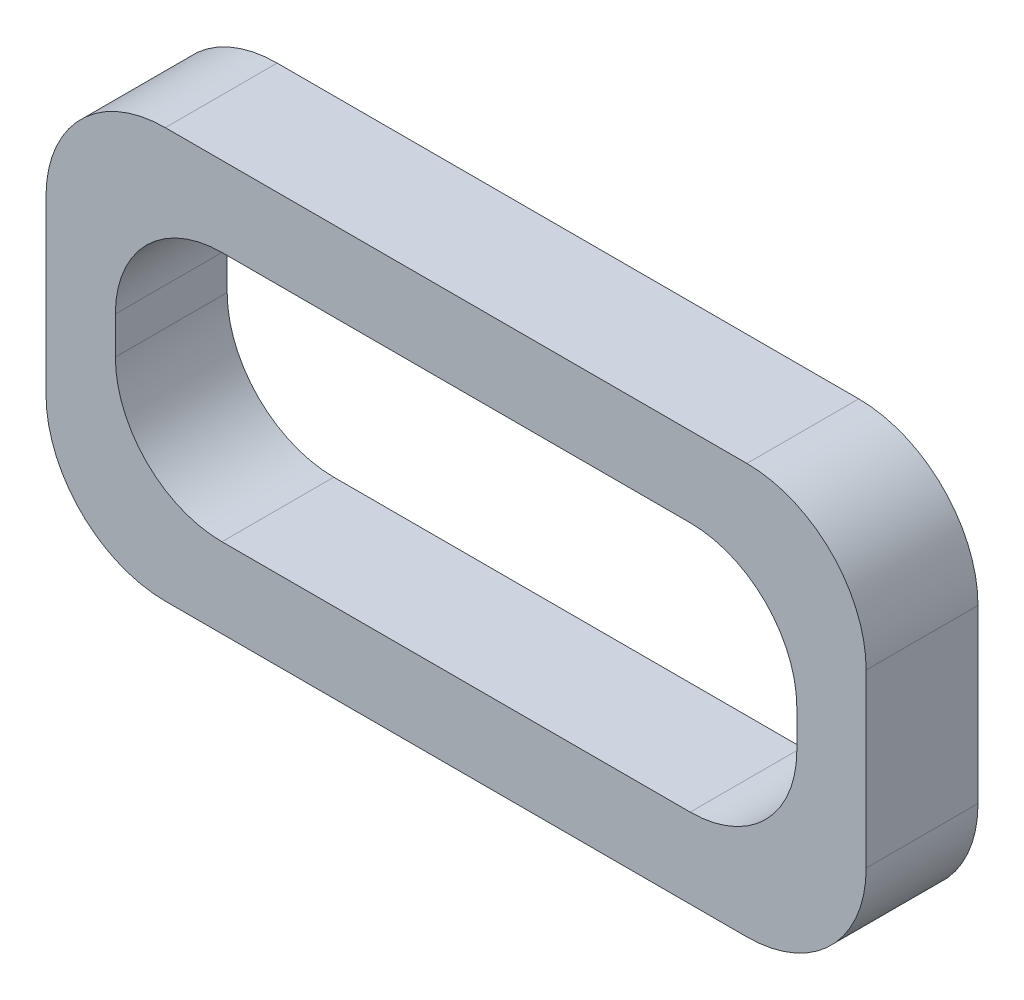
SolidWorks part; units mm, degrees
material "Silicon"
ref_plane "Front Plane" through (0, 0, 0) normal (0, 0, 1) x (1, 0, 0)
ref_plane "Top Plane" through (0, 0, 0) normal (0, 1, 0) x (1, 0, 0)
ref_plane "Right Plane" through (0, 0, 0) normal (1, 0, 0) x (0, 0, -1)
sketch "Sketch1" plane through (0, 0, 0) normal (0, 0, 1) x (1, 0, 0)
  line L8 (-3.9, -2.75) -> (3.9, -2.75)
  line L9 (5.5, -1.15) -> (5.5, 1.15)
  line L10 (3.9, 2.75) -> (-3.9, 2.75)
  line L11 (-5.5, 1.15) -> (-5.5, -1.15)
  line L16 (4.57, -0.25) -> (4.57, 0.25)
  line L17 (3.14, 1.68) -> (-3.14, 1.68)
  line L18 (-4.57, 0.25) -> (-4.57, -0.25)
  line L19 (-3.14, -1.68) -> (3.14, -1.68)
  arc A8 (3.9, -2.75) -> (5.5, -1.15) centre (3.9, -1.15) ccw
  arc A9 (5.5, 1.15) -> (3.9, 2.75) centre (3.9, 1.15) ccw
  arc A10 (-3.9, 2.75) -> (-5.5, 1.15) centre (-3.9, 1.15) ccw
  arc A11 (-5.5, -1.15) -> (-3.9, -2.75) centre (-3.9, -1.15) ccw
  arc A16 (3.14, -1.68) -> (4.57, -0.25) centre (3.14, -0.25) ccw
  arc A17 (4.57, 0.25) -> (3.14, 1.68) centre (3.14, 0.25) ccw
  arc A18 (-3.14, 1.68) -> (-4.57, 0.25) centre (-3.14, 0.25) ccw
  arc A19 (-4.57, -0.25) -> (-3.14, -1.68) centre (-3.14, -0.25) ccw
  point P2 (4.57, 0)
  point P17 (5.5, 0)
  point P22 (0, 1.68)
  point P26 (0, 2.75)
  dimension "D3" = 1.6
  dimension "D4" = 1.43
  dimension "D1" = 5.5
  dimension "D2" = 11
  dimension "D5" = 3.36
  dimension "D6" = 9.14
extrude "Boss-Extrude1" add sketch "Sketch1" along normal blind 1.5
